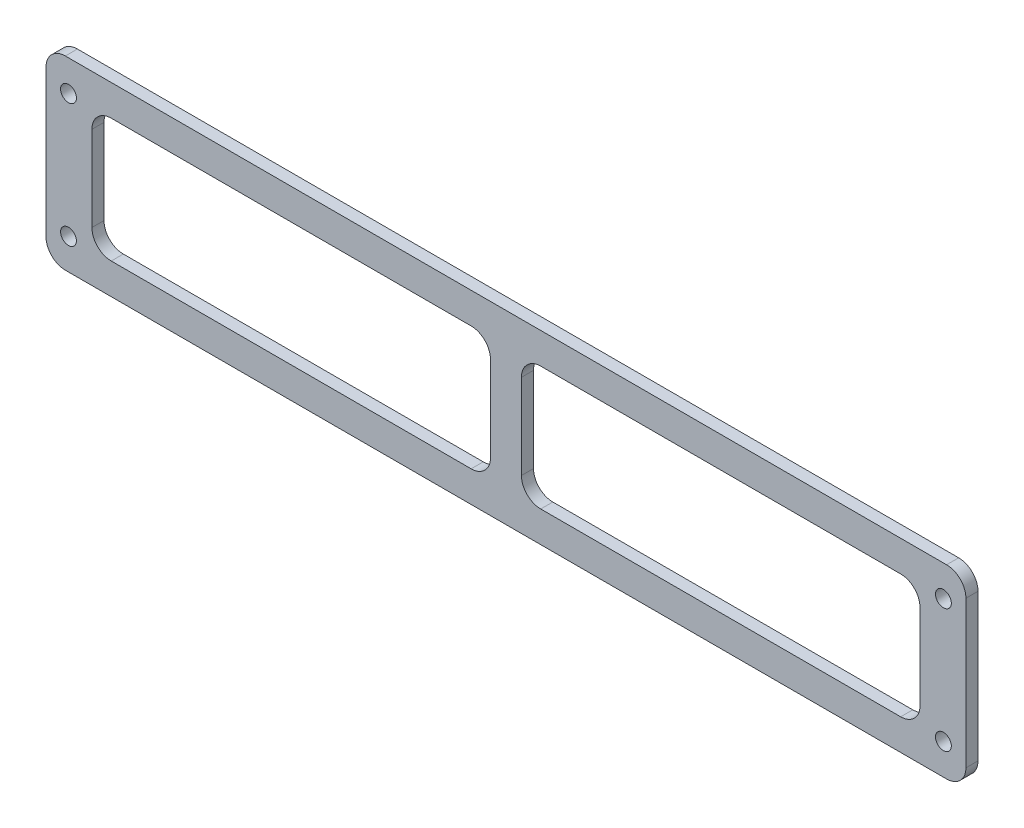
SolidWorks part; units mm, degrees
ref_plane "Front Plane" through (0, 0, 0) normal (0, 0, 1) x (1, 0, 0)
ref_plane "Top Plane" through (0, 0, 0) normal (0, 1, 0) x (1, 0, 0)
ref_plane "Right Plane" through (0, 0, 0) normal (1, 0, 0) x (0, 0, -1)
sketch "Sketch1" plane through (0, 0, 0) normal (0, 0, 1) x (1, 0, 0)
  line L0 (0, 0) -> (0, -50000) construction
  line L1 (119, -24) -> (-119, -24)
  line L2 (119, -24) -> (119, 24)
  line L3 (119, 24) -> (-119, 24)
  line L4 (-119, -24) -> (-119, 24)
  line L5 (119, -24) -> (-119, 24) construction
  line L6 (119, 24) -> (-119, -24) construction
  line L7 (113.175, 16) -> (-113.175, 16) construction
  line L8 (113.175, 16) -> (113.175, -16) construction
  line L9 (113.175, -16) -> (-113.175, -16) construction
  line L10 (-113.175, 16) -> (-113.175, -16) construction
  line L11 (113.175, 16) -> (-113.175, -16) construction
  line L12 (113.175, -16) -> (-113.175, 16) construction
  line L13 (-107.125, 16) -> (-4, 16)
  line L14 (-107.125, 16) -> (-107.125, -16)
  line L15 (-107.125, -16) -> (-4, -16)
  line L16 (-4, 16) -> (-4, -16)
  line L17 (107.125, -16) -> (4, -16)
  line L18 (4, 16) -> (4, -16)
  line L19 (107.125, 16) -> (4, 16)
  line L20 (107.125, 16) -> (107.125, -16)
  circle A0 centre (-113.175, 16) radius 2.05
  circle A1 centre (-113.175, -16) radius 2.05
  circle A2 centre (113.175, 16) radius 2.05
  circle A3 centre (113.175, -16) radius 2.05
  circle A4 centre (-113.175, 16) radius 6.05 construction
  circle A5 centre (-113.175, -16) radius 6.05 construction
  circle A6 centre (113.175, 16) radius 6.05 construction
  circle A7 centre (113.175, -16) radius 6.05 construction
  point P0 (0, 0)
  point P6 (0, 0)
  dimension "D5" = 4.1
  dimension "D1" = 238
  dimension "D2" = 48
  dimension "D3" = 226.35
  dimension "D4" = 32
  dimension "D7" = 4
  dimension "D6" = 4
extrude "Boss-Extrude1" add sketch "Sketch1" along normal blind 3.125
fillet "Fillet1" radius 5 12 edges at (-107.125, -16, 1.5625) (-107.125, 16, 1.5625) (-4, 16, 1.5625) (-4, -16, 1.5625) (107.125, -16, 1.5625) (107.125, 16, 1.5625) (4, 16, 1.5625) (4, -16, 1.5625) (119, 24, 1.5625) (119, -24, 1.5625) (-119, -24, 1.5625) (-119, 24, 1.5625)
